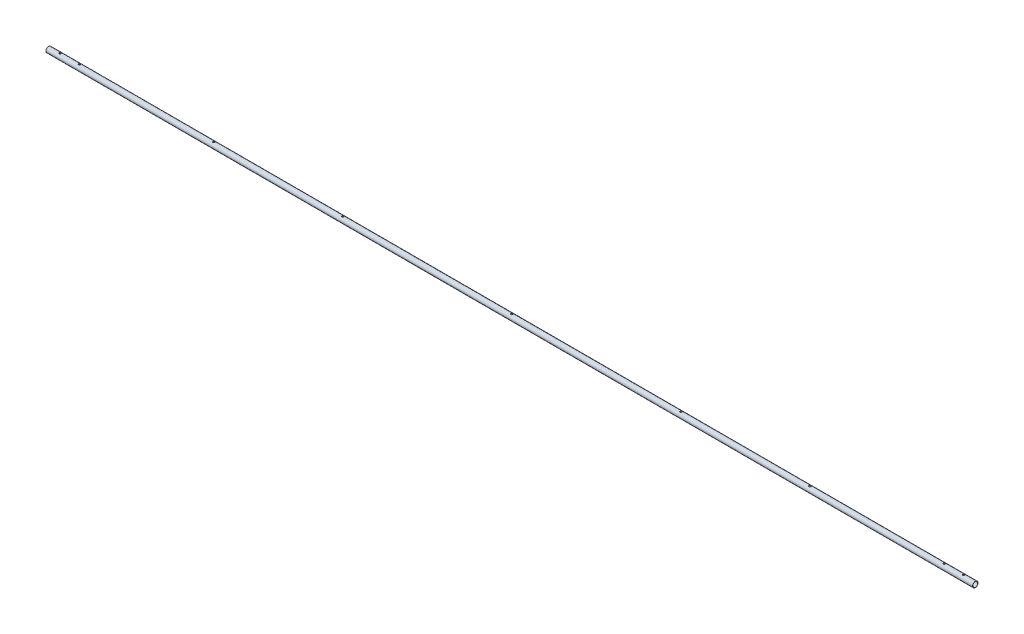
SolidWorks part; units mm, degrees
material "Galvanized Steel"
ref_plane "Front Plane" through (0, 0, 0) normal (0, 0, 1) x (1, 0, 0)
ref_plane "Top Plane" through (0, 0, 0) normal (0, 1, 0) x (1, 0, 0)
ref_plane "Right Plane" through (0, 0, 0) normal (1, 0, 0) x (0, 0, -1)
sketch "Sketch1" plane through (0, 0, 0) normal (1, 0, 0) x (0, 0, -1)
  circle A0 centre (0, 0) radius 7.8994
  circle A1 centre (0, 0) radius 8.9662
  dimension "D1" = 15.7988
  dimension "D2" = 17.9324
extrude "Boss-Extrude1" add sketch "Sketch1" along normal blind 3048
sketch "Sketch2" plane through (0, 0, 0) normal (0, 1, 0) x (1, 0, 0)
  line L0 (0, 8.9662) -> (0, -8.9662) construction
  line L1 (3048, -8.9662) -> (3048, 8.9662) construction
  circle A0 centre (38.1, 0) radius 3.175
  circle A1 centre (3009.9, 0) radius 3.175
  circle A2 centre (101.6, 0) radius 3.175
  circle A3 centre (2946.4, 0) radius 3.175
  dimension "D1" = 6.35
  dimension "D3" = 6.35
  dimension "D5" = 6.35
  dimension "D7" = 6.35
  dimension "D2" = 38.1
  dimension "D4" = 38.1
  dimension "D6" = 101.6
  dimension "D8" = 101.6
sketch "Sketch3" plane through (0, 0, 0) normal (0, 1, 0) x (1, 0, 0)
  line L0 (0, 8.9662) -> (0, -8.9662) construction
  line L1 (3048, -8.9662) -> (3048, 8.9662) construction
  circle A0 centre (1524, 0) radius 3.175
  circle A1 centre (2080.26, 0) radius 3.175
  circle A2 centre (967.74, 0) radius 3.175
  circle A3 centre (543.56, 0) radius 3.175
  circle A4 centre (2504.44, 0) radius 3.175
  dimension "D1" = 6.35
  dimension "D3" = 556.26
  dimension "D4" = 556.26
  dimension "D5" = 543.56
  dimension "D6" = 543.56
  dimension "D2" = 1524
extrude "Cut-Extrude2" cut sketch "Sketch3" against normal through all and the other way through all
extrude "Cut-Extrude5" cut sketch "Sketch2" against normal through all and the other way through all
ref_plane "Plane1" through (0, -6.1186, 6.5541) normal (0, -0.6824, 0.731) x (1, 0, 0)
